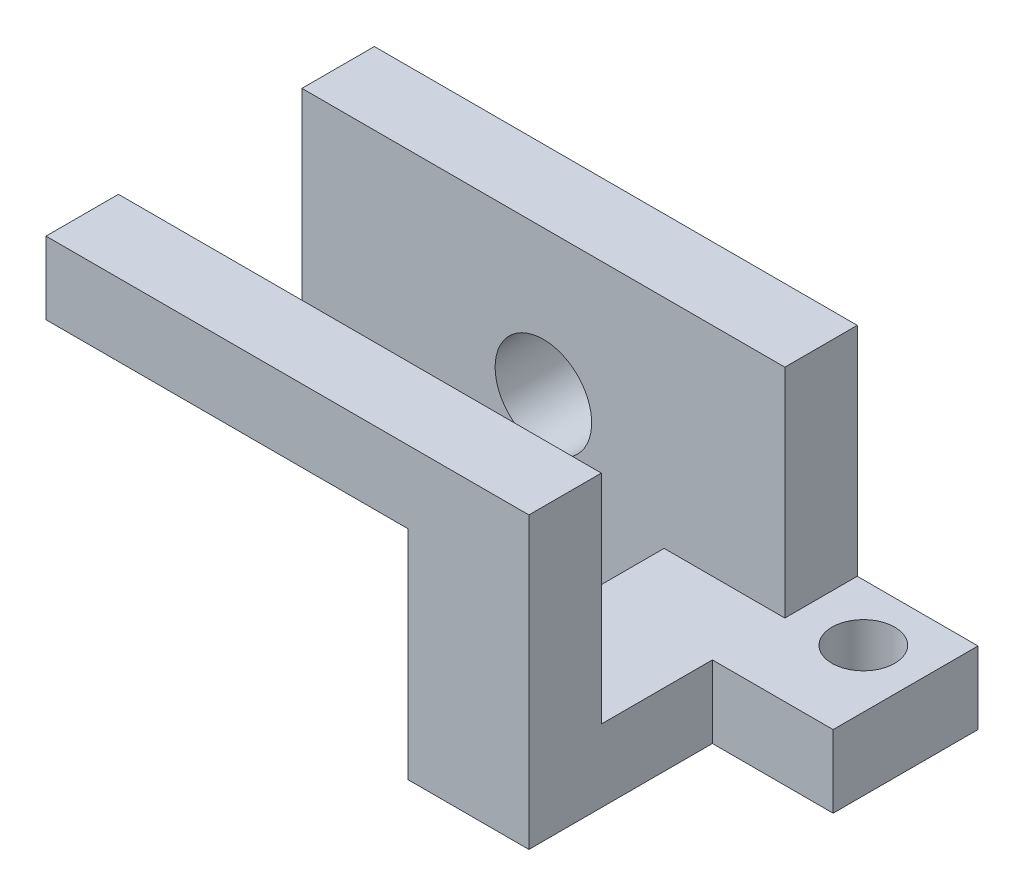
SolidWorks part; units mm, degrees
ref_plane "Front Plane" through (0, 0, 0) normal (0, 0, 1) x (1, 0, 0)
ref_plane "Top Plane" through (0, 0, 0) normal (0, 1, 0) x (1, 0, 0)
ref_plane "Right Plane" through (0, 0, 0) normal (1, 0, 0) x (0, 0, -1)
sketch "Sketch1" plane through (0, 0, 0) normal (0, 0, 1) x (1, 0, 0)
  line L1 (0, 0) -> (-100, 0)
  line L2 (0, 0) -> (0, 60)
  line L3 (0, 60) -> (-100, 60)
  line L4 (-100, 0) -> (-100, 60)
  dimension "D1" = 100
  dimension "D2" = 60
extrude "Boss-Extrude1" add sketch "Sketch1" along normal blind 15
sketch "Sketch2" plane through (0, 0, 15) normal (0, 0, 1) x (1, 0, 0)
  line L1 (0, 0) -> (-25, 0)
  line L2 (0, 0) -> (0, 15)
  line L3 (0, 15) -> (-25, 15)
  line L4 (-25, 0) -> (-25, 15)
  dimension "D1" = 15
  dimension "D2" = 25
extrude "Boss-Extrude2" add sketch "Sketch2" along normal blind 38
sketch "Sketch4" plane through (0, 0, 53) normal (0, 0, 1) x (1, 0, 0)
  line L1 (0, 0) -> (-100, 0)
  line L2 (0, 0) -> (0, 60)
  line L3 (0, 60) -> (-100, 60)
  line L4 (-100, 0) -> (-100, 60)
extrude "Boss-Extrude3" add sketch "Sketch4" along normal blind 15
sketch "Sketch5" plane through (0, 0, 53) normal (0, 0, -1) x (-1, 0, 0)
  line L0 (100, 60) -> (100, 0) construction
  line L1 (25, 0) -> (100, 0)
  line L2 (25, 0) -> (25, 45)
  line L3 (25, 45) -> (100, 45)
  line L4 (100, 0) -> (100, 45)
  line L5 (0, 60) -> (100, 60) construction
  dimension "D1" = 15
extrude "Cut-Extrude1" cut sketch "Sketch5" against normal blind 15
sketch "Sketch6" plane through (0, 0, 0) normal (1, 0, 0) x (0, 0, -1)
  line L0 (-53, 15) -> (-15, 15) construction
  line L1 (0, 0) -> (-30, 0)
  line L2 (0, 0) -> (0, 15)
  line L3 (0, 15) -> (-30, 15)
  line L4 (-30, 0) -> (-30, 15)
  dimension "D1" = 30
extrude "Boss-Extrude4" add sketch "Sketch6" along normal blind 25
sketch "Sketch7" plane through (0, 15, 0) normal (0, 1, 0) x (1, 0, 0)
  line L0 (25, 0) -> (25, -30) construction
  line L1 (-25, -53) -> (-25, -15) construction
  line L2 (25, -30) -> (0, -30) construction
  line L3 (25, 0) -> (0, 0) construction
  circle A0 centre (13, -11.7414) radius 6.5
  dimension "D2" = 13
  dimension "D1" = 12
  dimension "D3" = 50
  dimension "D4" = 30
extrude "Cut-Extrude2" cut sketch "Sketch7" against normal blind 15
sketch "Sketch8" plane through (0, 0, 0) normal (0, 0, -1) x (-1, 0, 0)
  line L0 (100, 0) -> (-25, 0) construction
  line L2 (100, 60) -> (100, 0) construction
  circle A0 centre (50, 30) radius 10
  point P6 (-75.9426, 76.9441)
  dimension "D3" = 20
  dimension "D1" = 30
  dimension "D2" = 50
extrude "Cut-Extrude3" cut sketch "Sketch8" against normal blind 15
